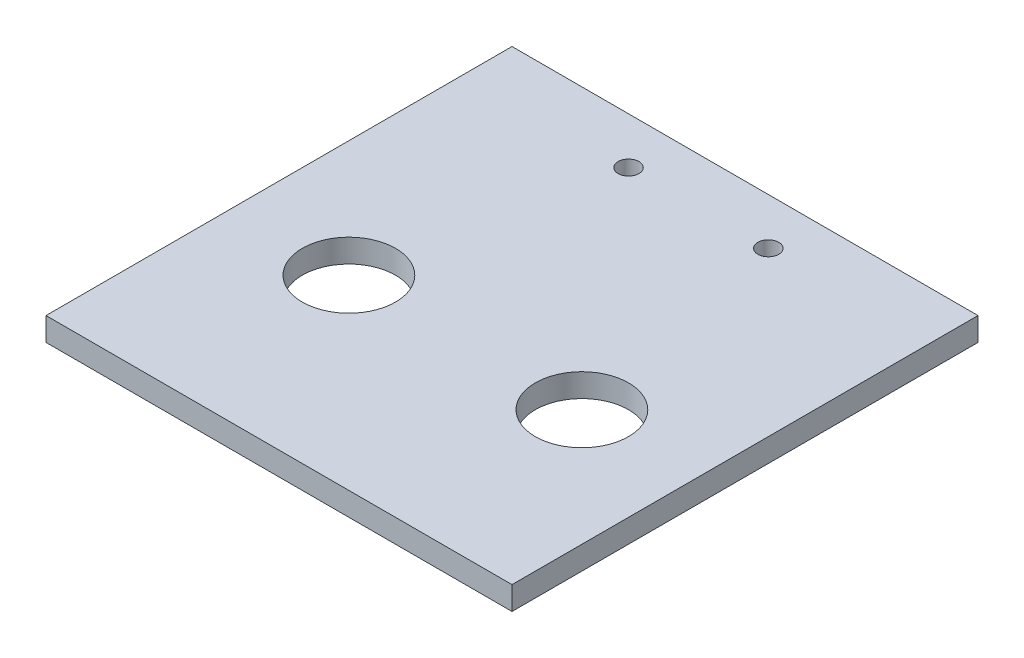
SolidWorks part; units mm, degrees
ref_plane "Front" through (0, 0, 0) normal (0, 0, 1) x (1, 0, 0)
ref_plane "Top" through (0, 0, 0) normal (0, 1, 0) x (1, 0, 0)
ref_plane "Right" through (0, 0, 0) normal (1, 0, 0) x (0, 0, -1)
sketch "Sketch1" plane through (0, 0, 0) normal (0, 1, 0) x (1, 0, 0)
  line L0 (15.875, 25.4) -> (47.625, 25.4) construction
  line L1 (0, 0) -> (63.5, 0)
  line L2 (0, 0) -> (0, 63.5)
  line L3 (0, 63.5) -> (63.5, 63.5)
  line L4 (63.5, 0) -> (63.5, 63.5)
  line L5 (31.75, 25.4) -> (31.75, 0) construction
  line L6 (31.75, 25.4) -> (31.75, 57.15) construction
  line L7 (22.225, 57.15) -> (41.275, 57.15) construction
  circle A0 centre (15.875, 25.4) radius 6.35
  circle A1 centre (47.625, 25.4) radius 6.35
  circle A2 centre (22.225, 57.15) radius 1.4224
  circle A3 centre (41.275, 57.15) radius 1.4224
  dimension "D2" = 12.7
  dimension "D4" = 2.8448
  dimension "D5" = 2.8448
  dimension "D1" = 31.75
  dimension "D3" = 25.4
  dimension "D6" = 31.75
  dimension "D7" = 63.5
  dimension "D8" = 63.5
  dimension "D9" = 19.05
extrude "Boss-Extrude1" add sketch "Sketch1" along normal blind 3.175
